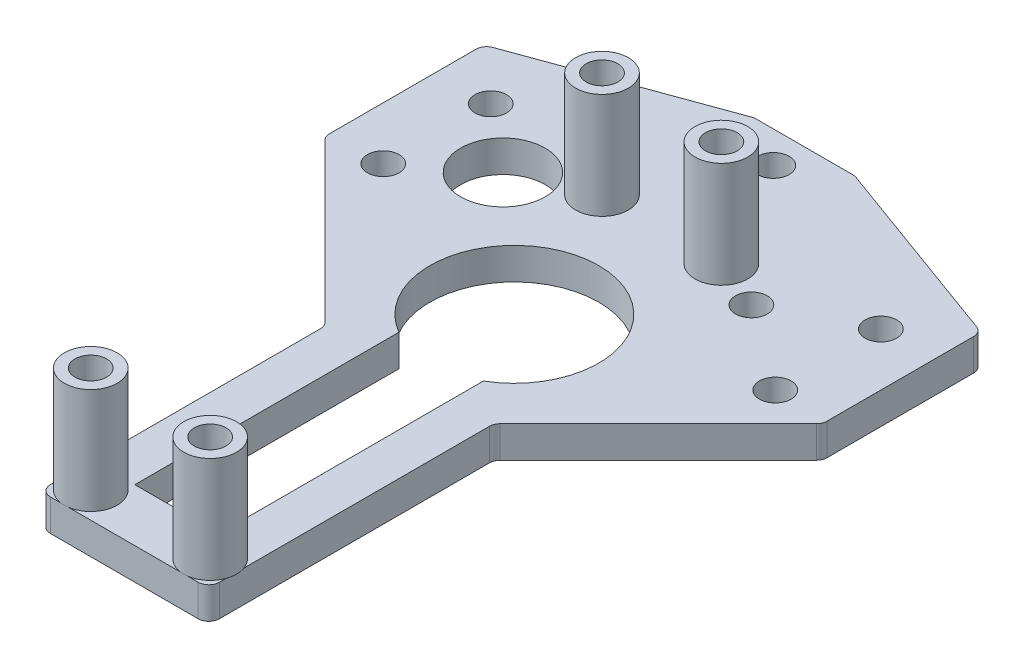
SolidWorks part; units mm, degrees
ref_plane "Front Plane" through (0, 0, 0) normal (0, 0, 1) x (1, 0, 0)
ref_plane "Top Plane" through (0, 0, 0) normal (0, 1, 0) x (1, 0, 0)
ref_plane "Right Plane" through (0, 0, 0) normal (1, 0, 0) x (0, 0, -1)
sketch "Sketch2" plane through (0, 0, 0) normal (0, 1, 0) x (1, 0, 0)
  line L0 (-8.2943, -10.7206) -> (7.7057, -10.7206)
  line L1 (-8.2943, -10.7206) -> (-8.2943, 16.2794)
  line L2 (7.7057, -10.7206) -> (7.7057, 16.2794)
  line L4 (-4.2943, -5.7206) -> (3.7057, -5.7206)
  line L5 (-4.2943, -5.7206) -> (-4.2943, 19.2794)
  line L6 (-8.2943, 16.2794) -> (-23.8506, 31.8357)
  line L7 (-23.8506, 31.8357) -> (-23.8506, 46.8357)
  line L8 (-23.8506, 46.8357) -> (-5.0568, 53.6761)
  line L9 (-5.0568, 53.6761) -> (4.4682, 53.6761)
  line L10 (4.4682, 53.6761) -> (23.2621, 46.8357)
  line L11 (23.2621, 46.8357) -> (23.2621, 31.8357)
  line L12 (23.2621, 31.8357) -> (7.7057, 16.2794)
  line L13 (3.7057, -5.7206) -> (3.7057, 19.2794)
  arc A0 (3.7057, 19.2794) -> (-4.2943, 19.2794) centre (-0.2943, 26.2076) ccw
  circle A3 centre (-18.6731, 42.3536) radius 1.5
  circle A4 centre (-18.8506, 32.3552) radius 1.5
  circle A5 centre (18.2621, 42.3536) radius 1.5
  circle A6 centre (18.2621, 32.3552) radius 1.5
  circle A7 centre (10.1516, 38.205) radius 1.5
  circle A8 centre (-0.2434, 50.6766) radius 1.5
  circle A9 centre (-12.4702, 37.3014) radius 4
  point P1 (0, 0)
  point P35 (-0.2943, 53.6761)
  point P47 (-0.2943, -5.7206)
  dimension "D13" = 3
  dimension "16" = 16
  dimension "D16" = 3
  dimension "D21" = 8
  dimension "D2" = 16
  dimension "D3" = 22
  dimension "D4" = 15
  dimension "D5" = 110
  dimension "D6" = 20
  dimension "D7" = 135
  dimension "D8" = 135
  dimension "D9" = 3
  dimension "D10" = 25
  dimension "D11" = 8
  dimension "D12" = 4
  dimension "D14" = 10
  dimension "D15" = 10
  dimension "D17" = 3
  dimension "D18" = 5
  dimension "D19" = 5
  dimension "D20" = 5
  dimension "D22" = 8
  dimension "D23" = 5
extrude "Boss-Extrude1" add sketch "Sketch2" along normal blind 3
fillet "Fillet1" radius 1 10 edges at (23.2621, 1.5, -46.8357) (4.4682, 1.5, -53.6761) (-5.0568, 1.5, -53.6761) (-23.8506, 1.5, -46.8357) (-23.8506, 1.5, -31.8357) (-8.2943, 1.5, -16.2794) (-8.2943, 1.5, 10.7206) (7.7057, 1.5, 10.7206) (23.2621, 1.5, -31.8357) (7.7057, 1.5, -16.2794)
sketch "Sketch3" plane through (0, 3, 0) normal (0, 1, 0) x (1, 0, 0)
  line L0 (-5.9443, -8.2424) -> (5.3557, -8.2424) construction
  line L1 (-4.2943, -5.7206) -> (3.7057, -5.7206) construction
  line L2 (-5.9443, 40.1576) -> (5.3557, 40.1576) construction
  circle A0 centre (-5.9443, -8.2424) radius 2.5
  circle A1 centre (5.3557, -8.2424) radius 2.5
  circle A2 centre (-5.9443, -8.2424) radius 1.5
  circle A3 centre (5.3557, -8.2424) radius 1.5
  circle A4 centre (-5.9443, 40.1576) radius 2.5
  circle A5 centre (5.3557, 40.1576) radius 2.5
  circle A6 centre (-5.9443, 40.1576) radius 1.5
  circle A7 centre (5.3557, 40.1576) radius 1.5
  arc A8 (3.7057, 19.2794) -> (-4.2943, 19.2794) centre (-0.2943, 26.2076) ccw construction
  point P15 (-0.2943, -5.7206)
  point P18 (-0.2943, -8.2424)
  point P19 (-0.2943, 40.1576)
  dimension "D1" = 5
  dimension "D2" = 5
  dimension "D3" = 3
  dimension "D4" = 3
  dimension "D5" = 5
  dimension "D6" = 5
  dimension "D7" = 3
  dimension "D8" = 3
  dimension "D9" = 13.95
  dimension "D10" = 34.45
  dimension "D11" = 11.3
extrude "Boss-Extrude2" add sketch "Sketch3" along normal blind 10
